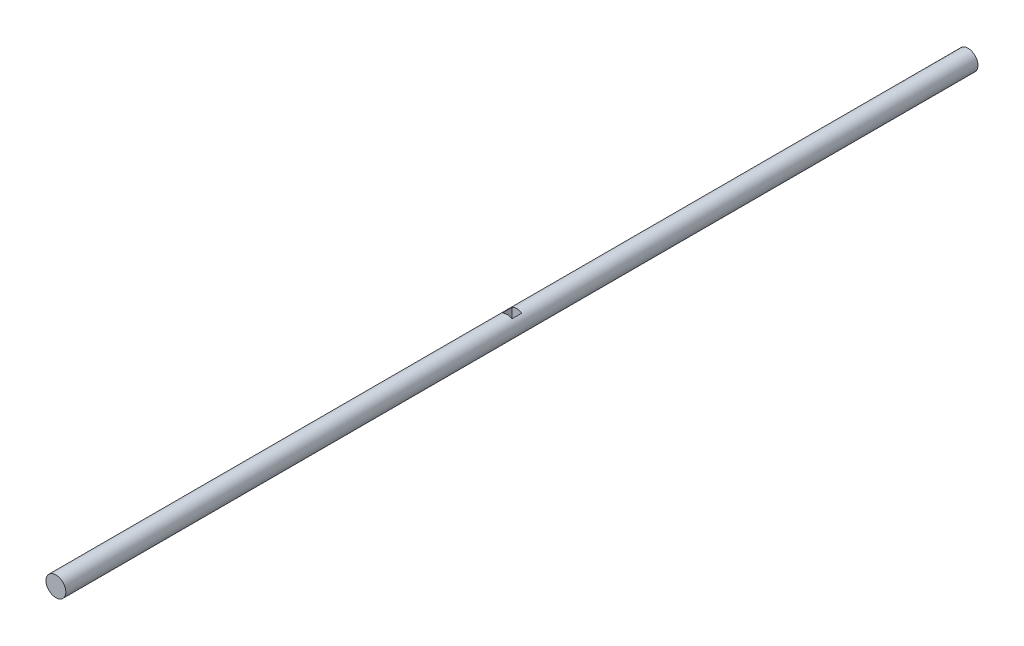
SolidWorks part; units mm, degrees
material "Balsa"
ref_plane "Alzado" through (0, 0, 0) normal (0, 0, 1) x (1, 0, 0)
ref_plane "Planta" through (0, 0, 0) normal (0, 1, 0) x (1, 0, 0)
ref_plane "Vista lateral" through (0, 0, 0) normal (1, 0, 0) x (0, 0, -1)
sketch "Croquis1" plane through (0, 0, 0) normal (0, 0, 1) x (1, 0, 0)
  circle A0 centre (0, 0) radius 2.5
  dimension "D1" = 5
extrude "Saliente-Extruir1" add sketch "Croquis1" along normal blind 230
sketch "Croquis2" plane through (0, 0, 0) normal (0, 1, 0) x (1, 0, 0)
  line L0 (0, -230) -> (0, 0) construction
  line L1 (-2.5, -230) -> (2.5, -230) construction
  line L3 (1.25, -113.75) -> (-1.25, -113.75)
  line L4 (1.25, -113.75) -> (1.25, -116.25)
  line L5 (1.25, -116.25) -> (-1.25, -116.25)
  line L6 (-1.25, -113.75) -> (-1.25, -116.25)
  line L7 (1.25, -113.75) -> (-1.25, -116.25) construction
  line L8 (1.25, -116.25) -> (-1.25, -113.75) construction
  point P5 (0, -115)
  dimension "D1" = 2.5
  dimension "D2" = 2.5
extrude "Cortar-Extruir1" cut sketch "Croquis2" against normal mid plane 10
ref_plane "Plano1" through (0, 2.5, 0) normal (0, 1, 0) x (1, 0, 0)
sketch "Croquis3" plane through (0, 2.5, 0) normal (0, 1, 0) x (1, 0, 0)
  line L0 (0, -113.75) -> (0, -116.25) construction
  line L1 (-1.25, -113.75) -> (1.25, -113.75) construction
  line L2 (1.25, -116.25) -> (-1.25, -116.25) construction
